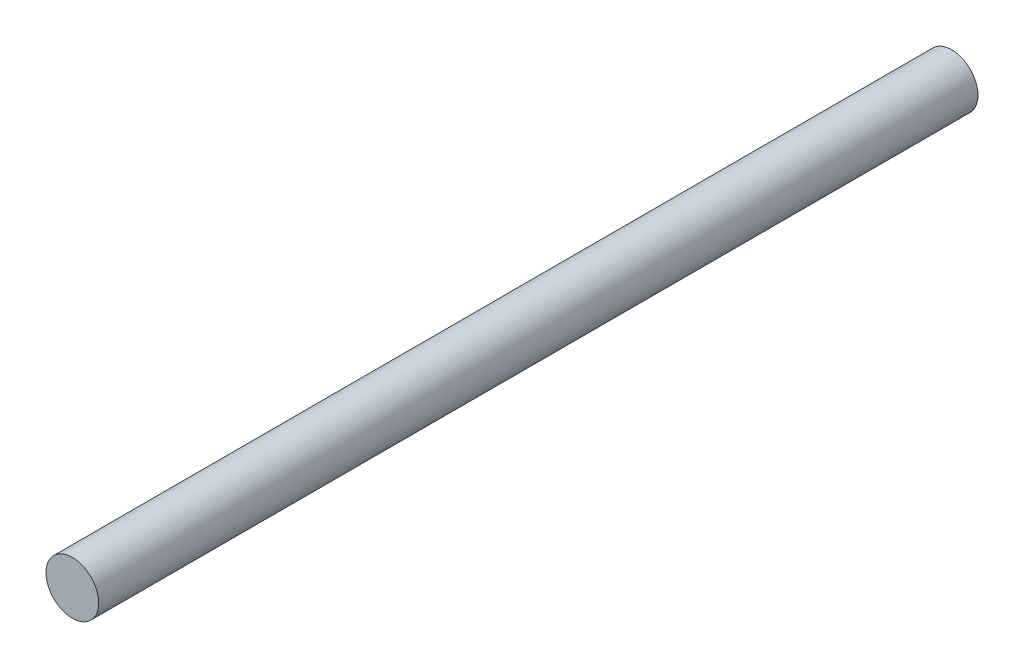
SolidWorks part; units mm, degrees
ref_plane "Plano frontal" through (0, 0, 0) normal (0, 0, 1) x (1, 0, 0)
ref_plane "Plano superior" through (0, 0, 0) normal (0, 1, 0) x (1, 0, 0)
ref_plane "Plano direito" through (0, 0, 0) normal (1, 0, 0) x (0, 0, -1)
sketch "Esboço1" plane through (0, 0, 0) normal (0, 0, 1) x (1, 0, 0)
  circle A0 centre (0, 0) radius 7.5
extrude "Ressalto-extrusão1" add sketch "Esboço1" along normal blind 250
